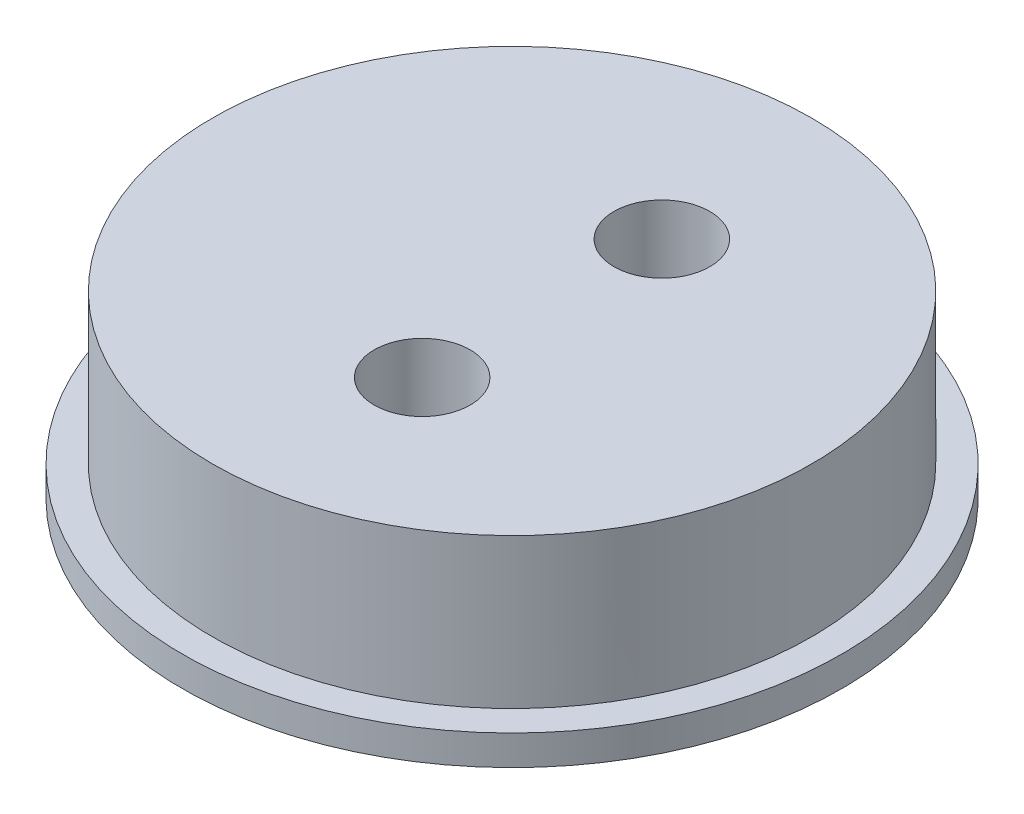
SolidWorks part; units mm, degrees
ref_plane "Front Plane" through (0, 0, 0) normal (0, 0, 1) x (1, 0, 0)
ref_plane "Top Plane" through (0, 0, 0) normal (0, 1, 0) x (1, 0, 0)
ref_plane "Right Plane" through (0, 0, 0) normal (1, 0, 0) x (0, 0, -1)
sketch "Sketch1" plane through (0, 0, 0) normal (0, 1, 0) x (1, 0, 0)
  line L0 (0, 0) -> (-1, 0) construction
  circle A1 centre (-1, 0) radius 10
  point P12 (0, 0)
  dimension "D3" = 20
  dimension "D2" = 1
extrude "Boss-Extrude1" add sketch "Sketch1" along normal blind 6
sketch "Sketch2" plane through (0, 0, 0) normal (0, -1, 0) x (1, 0, 0)
  line L0 (-12.8187, 0) -> (7.6603, 0) construction
  circle A0 centre (-1, 0) radius 11
  dimension "D2" = 22
  dimension "D1" = 1
extrude "Boss-Extrude2" add sketch "Sketch2" against normal blind 1
sketch "Sketch4" plane through (0, 6, 0) normal (0, 1, 0) x (1, 0, 0)
  line L0 (0, 8.8969) -> (0, -8.7328) construction
  circle A0 centre (0, 0) radius 4 construction
  circle A1 centre (0, 4) radius 1.6
  circle A2 centre (0, -4) radius 1.6
  dimension "D1" = 8
  dimension "D2" = 3.2
extrude "Cut-Extrude1" cut sketch "Sketch4" against normal through all
